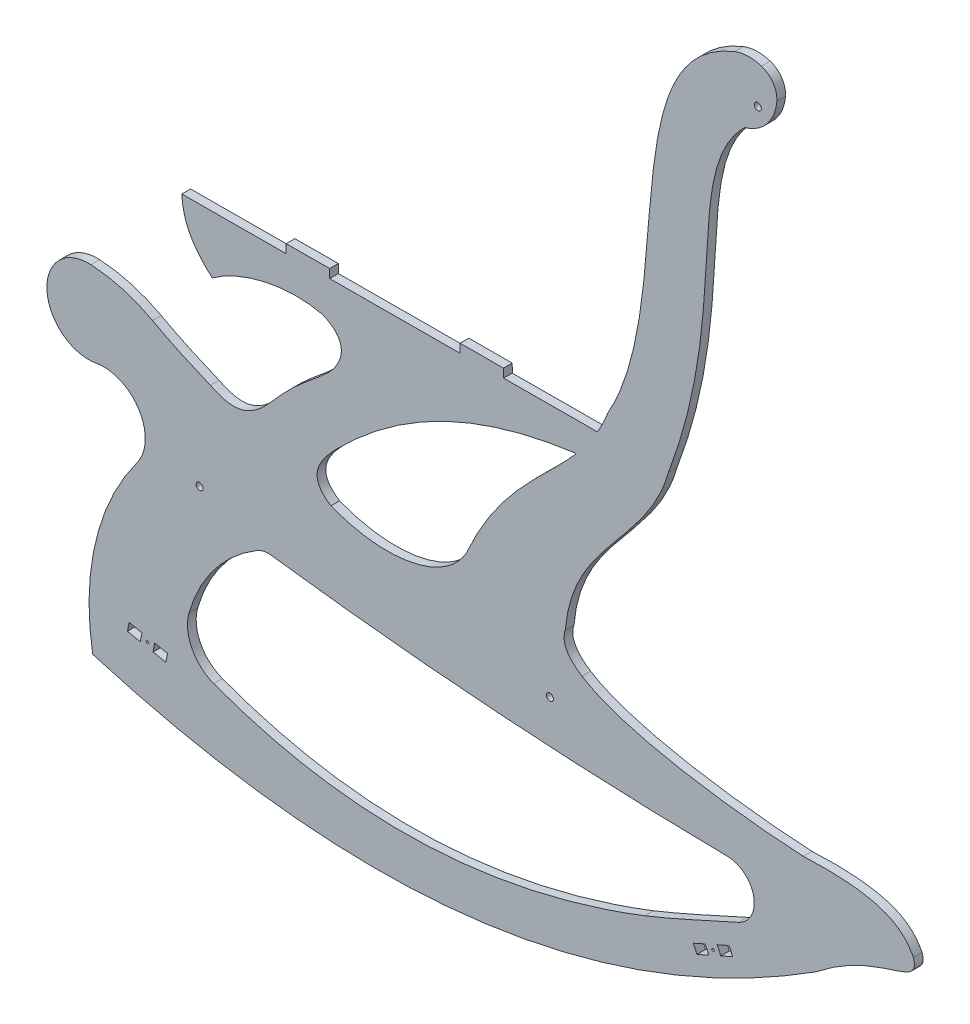
SolidWorks part; units mm, degrees
material "Teak"
ref_plane "Front Plane" through (0, 0, 0) normal (0, 0, 1) x (1, 0, 0)
ref_plane "Top Plane" through (0, 0, 0) normal (0, 1, 0) x (1, 0, 0)
ref_plane "Right Plane" through (0, 0, 0) normal (1, 0, 0) x (0, 0, -1)
sketch "Несущая боковая" plane through (0, 0, 0) normal (0, 0, 1) x (1, 0, 0)
  line L6 (398.785, -200.6515) -> (-79.2948, -202.7)
  arc A0 (568.0858, 187.1743) -> (604.9253, 231.748) centre (555.0835, 235.431) ccw
  arc A1 (604.9253, 231.748) -> (587.3016, 257.9076) centre (579.4885, 233.6276) ccw
  arc A2 (587.3016, 257.9076) -> (556.344, 256.9224) centre (573.2016, 214.0906) ccw
  arc A4 (-130.7033, -495.9282) -> (-177.7889, -420.4808) centre (-169.1009, -467.4752) ccw
  arc A7 (-130.7033, -495.9282) -> (-181.6944, -712.4375) centre (95.3308, -663.4217) ccw
  arc A8 (-183.8786, -325.353) -> (-177.7889, -420.4808) centre (-186.515, -373.2806) ccw
  arc A9 (-112.9747, -345.6094) -> (-183.8786, -325.353) centre (-193.0224, -491.581) ccw
  arc A10 (560.3467, -608.2215) -> (548.1989, -548.57) centre (547.8281, -579.7082) ccw
  arc A11 (23.5507, -511.1423) -> (548.1989, -548.57) centre (601.0308, 3887.8918) ccw
  arc A12 (7.2112, -514.4863) -> (-70.9864, -615.6156) centre (95.3308, -663.4217) ccw
  arc A13 (-70.9864, -615.6156) -> (-42.6063, -671.9817) centre (-26.3207, -628.4543) ccw
  arc A14 (23.5507, -511.1423) -> (7.2112, -514.4863) centre (20.2245, -536.4807) ccw
  spline S0 degree 3 poles (556.344, 256.9224) (413.4931, 200.7) (492.8039, -30.4464) (410.7267, -175.5993) knots 0.000401 0.000401 0.000401 0.000401 0.043478 0.043478 0.043478 0.043478
  spline S1 degree 3 poles (410.7267, -175.5993) (407.231, -184.6492) (403.2193, -192.9282) (398.785, -200.6515) knots 0.043478 0.043478 0.043478 0.043478 0.086957 0.086957 0.086957 0.086957
  spline S2 degree 3 poles (-79.2948, -202.7) (-78.5172, -227.7) (-66.7741, -249.7094) (-44.1772, -268.7587) knots 0.130435 0.130435 0.130435 0.130435 0.173913 0.173913 0.173913 0.173913
  spline S3 degree 3 poles (-44.1772, -268.7587) (-12.7058, -245.829) (38.9597, -231.7344) (82.6666, -241.804) knots 0.173913 0.173913 0.173913 0.173913 0.217391 0.217391 0.217391 0.217391
  spline S4 degree 3 poles (82.6666, -241.804) (105.6787, -251.6525) (111.2464, -268.6919) (94.2115, -290.7234) knots 0.217391 0.217391 0.217391 0.217391 0.26087 0.26087 0.26087 0.26087
  spline S5 degree 3 poles (94.2115, -290.7234) (87.1581, -299.8457) (74.9831, -308.4217) (61.0599, -320.5021) knots 0.26087 0.26087 0.26087 0.26087 0.304348 0.304348 0.304348 0.304348
  spline S6 degree 3 poles (61.0599, -320.5021) (47.3806, -331.8412) (34.8832, -345.2678) (22.8705, -359.1067) knots 0.304348 0.304348 0.304348 0.304348 0.347826 0.347826 0.347826 0.347826
  spline S7 degree 3 poles (22.8705, -359.1067) (-5.5844, -391.8897) (-25.5922, -386.6363) (-46.4172, -376.7876) knots 0.347826 0.347826 0.347826 0.347826 0.391304 0.391304 0.391304 0.391304
  spline S8 degree 3 poles (-46.4172, -376.7876) (-71.9902, -366.2219) (-92.784, -356.6815) (-112.9747, -345.6094) knots 0.391304 0.391304 0.391304 0.391304 0.434783 0.434783 0.434783 0.434783
  spline S14 degree 3 poles (-181.6944, -712.4375) (138.4622, -807.7317) (410.6911, -765.399) (650.1904, -612.5982) knots 0.652174 0.652174 0.652174 0.652174 0.695652 0.695652 0.695652 0.695652
  spline S15 degree 3 poles (650.1904, -612.5982) (721.7263, -555.1366) (771.3742, -572.8028) (761.971, -542.4383) knots 0.695652 0.695652 0.695652 0.695652 0.73913 0.73913 0.73913 0.73913
  spline S16 degree 3 poles (761.971, -542.4383) (749.9881, -518.2511) (723.1034, -500.8362) (635.2399, -505.0064) knots 0.73913 0.73913 0.73913 0.73913 0.782609 0.782609 0.782609 0.782609
  spline S17 degree 3 poles (635.2399, -505.0064) (572.992, -501.9328) (433.5503, -486.7788) (380.9104, -452.9037) knots 0.782609 0.782609 0.782609 0.782609 0.826087 0.826087 0.826087 0.826087
  spline S18 degree 3 poles (380.9104, -452.9037) (364.7659, -442.5143) (356.7862, -430.3638) (361.7026, -416.2609) knots 0.826087 0.826087 0.826087 0.826087 0.869565 0.869565 0.869565 0.869565
  spline S19 degree 3 poles (361.7026, -416.2609) (369.7577, -319.5618) (455.7474, -287.137) (480.2427, -200.3025) knots 0.869565 0.869565 0.869565 0.869565 0.913043 0.913043 0.913043 0.913043
  spline S20 degree 3 poles (480.2427, -200.3025) (553.5443, -5.6015) (495.01, 115.2768) (568.0858, 187.1743) knots 0.913043 0.913043 0.913043 0.913043 0.956522 0.956522 0.956522 0.956522
  spline S25 degree 3 poles (452.9574, -655.3702) (274.7112, -724.495) (109.7393, -728.981) (-42.6063, -671.9817) knots 0.555556 0.555556 0.555556 0.555556 0.666667 0.666667 0.666667 0.666667
  spline S26 degree 3 poles (560.3467, -608.2215) (524.5503, -623.9377) (490.7002, -640.4881) (452.9574, -655.3702) knots 0.444444 0.444444 0.444444 0.444444 0.555556 0.555556 0.555556 0.555556
  spline S31 degree 3 poles (97.4618, -368.9486) (168.6207, -296.3511) (255.442, -250.0892) (374.5085, -234.3308) knots 0.75 0.75 0.75 0.75 1 1 1 1
  spline S32 degree 3 poles (92.0908, -427.5464) (69.7947, -412.5311) (70.4905, -396.4567) (97.4618, -368.9486) knots 0.5 0.5 0.5 0.5 0.75 0.75 0.75 0.75
  spline S33 degree 3 poles (247.8827, -396.6458) (222.4754, -441.0979) (152.6914, -451.7196) (92.0908, -427.5464) knots 0.25 0.25 0.25 0.25 0.5 0.5 0.5 0.5
  spline S34 degree 3 poles (374.5085, -234.3308) (336.7044, -278.0035) (285.6362, -310.9643) (247.8827, -396.6458) knots 0 0 0 0 0.25 0.25 0.25 0.25
  dimension "D2" = 48
sketch "Боковая под поперечины" [suppressed] plane through (0, 0, 0) normal (0, 0, 1) x (1, 0, 0)
  line L15 (-159.6049, -346.9107) -> (-207.6507, -344.8161) construction
  line L16 (-207.6507, -344.8161) -> (-218.5759, -409.003)
  line L56 (-207.6507, -344.8161) -> (-159.6963, -346.9068)
  line L57 (-159.6963, -346.9068) -> (-148.2015, -350.3521)
  line L58 (-148.2015, -350.3521) -> (-104.2437, -369.6319)
  line L59 (-104.2437, -369.6319) -> (-95.353, -374.2095)
  line L60 (-95.353, -374.2095) -> (-51.5894, -393.9261)
  line L61 (-51.5894, -393.9261) -> (-42.3459, -397.7417)
  line L62 (-42.3459, -397.7417) -> (2.1537, -415.7357)
  line L63 (2.1537, -415.7357) -> (11.4455, -419.432)
  line L64 (11.4455, -419.432) -> (56.3986, -436.2612)
  line L65 (56.3986, -436.2612) -> (65.8381, -439.5619)
  line L66 (65.8381, -439.5619) -> (111.7403, -453.5971)
  line L67 (111.7403, -453.5971) -> (121.3499, -456.3643)
  line L68 (121.3499, -456.3643) -> (169.2689, -459.1514)
  line L69 (169.2689, -459.1514) -> (179.2066, -458.0374)
  line L70 (179.2066, -458.0374) -> (224.5179, -442.198)
  line L71 (224.5179, -442.198) -> (232.8956, -436.7378)
  line L72 (232.8956, -436.7378) -> (261.7321, -398.3651)
  line L73 (261.7321, -398.3651) -> (267.2053, -389.9959)
  line L74 (267.2053, -389.9959) -> (294.9373, -350.8177)
  line L75 (294.9373, -350.8177) -> (300.8954, -342.7864)
  line L76 (300.8954, -342.7864) -> (330.585, -305.0699)
  line L77 (330.585, -305.0699) -> (336.9867, -297.3877)
  line L78 (336.9867, -297.3877) -> (368.9263, -261.5566)
  line L79 (368.9263, -261.5566) -> (376.1332, -254.6241)
  line L80 (376.1332, -254.6241) -> (406.9239, -217.801)
  line L81 (406.9239, -217.801) -> (412.4436, -209.4624)
  line L82 (412.4436, -209.4624) -> (434.4129, -166.7851)
  line L83 (438.0837, -157.4832) -> (452.6073, -111.7332)
  line L84 (452.6073, -111.7332) -> (454.9033, -102.0003)
  line L85 (454.9033, -102.0003) -> (464.25, -54.9191)
  line L86 (464.25, -54.9191) -> (465.6878, -45.023)
  line L87 (465.6878, -45.023) -> (472.014, 2.5582)
  line L88 (472.014, 2.5582) -> (473.0512, 12.5043)
  line L89 (473.0512, 12.5043) -> (478.3742, 60.2082)
  line L90 (478.3742, 60.2082) -> (479.4656, 70.1485)
  line L91 (479.4656, 70.1485) -> (486.2184, 117.6711)
  line L92 (486.2184, 117.6711) -> (487.9962, 127.5118)
  line L93 (487.9962, 127.5118) -> (500.2801, 173.9134)
  line L94 (500.2801, 173.9134) -> (504.8877, 188.1882)
  line L95 (504.8877, 188.1882) -> (532.6089, 227.3741)
  line L96 (532.6089, 227.3741) -> (546.1164, 235.9502)
  line L97 (546.1164, 235.9502) -> (589.1375, 257.2382)
  line L99 (434.4129, -166.7851) -> (438.0837, -157.4832)
  arc A4 (568.0858, 187.1743) -> (604.9253, 231.748) centre (554.9668, 235.5274) ccw
  arc A7 (604.9253, 231.748) -> (589.1375, 257.2382) centre (579.4223, 233.5866) ccw
  arc A10 (604.9253, 231.748) -> (587.3016, 257.9076) centre (579.4885, 233.6276) ccw construction
  arc A11 (-121.8206, -474.4411) -> (-17.3364, -532.0713) centre (-58.8058, -483.7252) ccw
  arc A12 (7.2112, -514.4863) -> (-17.3364, -532.0713) centre (95.3308, -663.4217) ccw
  arc A13 (23.5507, -511.1423) -> (7.2112, -514.4863) centre (20.2245, -536.4807) ccw
  arc A15 (-121.8206, -474.4411) -> (-177.7889, -420.4808) centre (-169.1009, -467.4752) ccw
  arc A16 (23.5507, -511.1423) -> (341.0431, -541.2606) centre (601.0308, 3887.8918) ccw
  arc A17 (-130.7033, -495.9282) -> (-177.7889, -420.4808) centre (-169.1009, -467.4752) ccw construction
  arc A18 (-183.8786, -325.353) -> (-177.7889, -420.4808) centre (-186.515, -373.2806) ccw construction
  arc A19 (-218.5759, -409.003) -> (-177.7889, -420.4808) centre (-186.515, -373.2806) ccw
  arc A20 (23.5507, -511.1423) -> (548.1989, -548.57) centre (601.0308, 3887.8918) ccw construction
  arc A21 (23.5507, -511.1423) -> (7.2112, -514.4863) centre (20.2245, -536.4807) ccw construction
  arc A22 (7.2112, -514.4863) -> (-70.9864, -615.6156) centre (95.3308, -663.4217) ccw construction
  arc A23 (341.0431, -541.2606) -> (375.7523, -454.4299) centre (343.931, -492.0624) ccw
  spline S13 degree 3 poles (375.7523, -454.4299) (361.34, -442.2431) (355.1113, -429.3811) (361.7026, -416.2609) knots 0.5 0.5 0.5 0.5 0.533333 0.533333 0.533333 0.533333
  spline S14 degree 3 poles (361.7026, -416.2609) (369.7577, -319.5618) (455.7474, -287.137) (480.2427, -200.3025) knots 0.533333 0.533333 0.533333 0.533333 0.566667 0.566667 0.566667 0.566667
  spline S15 degree 3 poles (480.2427, -200.3025) (553.5444, -5.6014) (495.0101, 115.2768) (568.0858, 187.1743) knots 0.566667 0.566667 0.566667 0.566667 0.6 0.6 0.6 0.6
  point P66 (608.2751, 264.1653)
  point P67 (553.7309, 240.2756)
  point P74 (-221.3236, -344.22)
  dimension "D1" = 48
  dimension "D2" = 12
  dimension "D3" = 10
  dimension "D10" = 16
  dimension "D11" = 15
extrude "Несущая" add sketch "Несущая боковая" along normal blind 10
extrude "Боковая" [suppressed] add sketch "Боковая под поперечины" along normal blind 10
sketch "Sketch3" [suppressed] plane through (0, 0, 0) normal (0, 0, 1) x (1, 0, 0)
  line L0 (546.1164, 235.9502) -> (589.1375, 257.2382) construction
  line L2 (-206.3501, -396.7709) -> (-202.6586, -375.0829)
  line L3 (-216.2083, -395.093) -> (-212.5168, -373.4049)
  line L6 (-216.2083, -395.093) -> (-206.3501, -396.7709)
  line L10 (-207.6507, -344.8161) -> (-194.6631, -345.3823) construction
  line L11 (-207.6507, -344.8161) -> (-208.0863, -354.8066) construction
  line L12 (-159.6963, -346.9068) -> (-160.1319, -356.8973) construction
  line L13 (-208.0863, -354.8066) -> (-195.0986, -355.3728) construction
  line L14 (-194.6631, -345.3823) -> (-195.0986, -355.3728)
  line L15 (-172.684, -346.3405) -> (-173.1195, -356.331)
  line L16 (-173.1195, -356.331) -> (-160.1319, -356.8973) construction
  line L17 (-195.0986, -355.3728) -> (-173.1195, -356.331)
  line L18 (-172.684, -346.3405) -> (-159.6963, -346.9068) construction
  line L19 (-194.6631, -345.3823) -> (-172.684, -346.3405)
  line L37 (-136.2963, -355.5737) -> (-140.3129, -364.7316)
  line L38 (-116.149, -364.4103) -> (-120.1656, -373.5681)
  line L40 (-152.2182, -359.51) -> (-140.3129, -364.7316) construction
  line L41 (-116.149, -364.4103) -> (-104.2437, -369.6319) construction
  line L42 (-140.3129, -364.7316) -> (-120.1656, -373.5681)
  line L43 (-104.2437, -369.6319) -> (-108.2603, -378.7897) construction
  line L44 (-120.1656, -373.5681) -> (-108.2603, -378.7897) construction
  line L45 (-148.2015, -350.3521) -> (-136.2963, -355.5737) construction
  line L46 (-136.2963, -355.5737) -> (-116.149, -364.4103)
  line L47 (-148.2015, -350.3521) -> (-152.2182, -359.51) construction
  line L48 (-104.2437, -369.6319) -> (-148.2015, -350.3521) construction
  line L49 (-63.442, -388.5862) -> (-67.5496, -397.7036)
  line L50 (-83.5003, -379.5494) -> (-63.442, -388.5862)
  line L51 (-83.5003, -379.5494) -> (-87.608, -388.6668)
  line L52 (-63.442, -388.5862) -> (-51.5894, -393.9261) construction
  line L53 (-99.4606, -383.3269) -> (-87.608, -388.6668) construction
  line L54 (-51.5894, -393.9261) -> (-55.697, -403.0436) construction
  line L55 (-95.353, -374.2095) -> (-83.5003, -379.5494) construction
  line L56 (-87.608, -388.6668) -> (-67.5496, -397.7036)
  line L57 (-67.5496, -397.7036) -> (-55.697, -403.0436) construction
  line L58 (-95.353, -374.2095) -> (-99.4606, -383.3269) construction
  line L59 (-34.0427, -411.8858) -> (-13.647, -420.1331)
  line L60 (-30.2939, -402.615) -> (-9.8983, -410.8623)
  line L61 (-42.3459, -397.7417) -> (-30.2939, -402.615) construction
  line L62 (-9.8983, -410.8623) -> (2.1537, -415.7357) construction
  line L63 (-46.0946, -407.0124) -> (-34.0427, -411.8858) construction
  line L64 (-9.8983, -410.8623) -> (-13.647, -420.1331)
  line L65 (-42.3459, -397.7417) -> (-46.0946, -407.0124) construction
  line L66 (-13.647, -420.1331) -> (-1.595, -425.0064) construction
  line L67 (-30.2939, -402.615) -> (-34.0427, -411.8858)
  line L68 (2.1537, -415.7357) -> (-1.595, -425.0064) construction
  line L69 (44.2238, -431.7033) -> (40.7177, -441.0685)
  line L70 (56.3986, -436.2612) -> (52.8925, -445.6264) construction
  line L71 (23.6203, -423.9899) -> (44.2238, -431.7033)
  line L72 (23.6203, -423.9899) -> (20.1142, -433.3551)
  line L73 (7.9394, -428.7972) -> (20.1142, -433.3551) construction
  line L74 (11.4455, -419.432) -> (23.6203, -423.9899) construction
  line L75 (44.2238, -431.7033) -> (56.3986, -436.2612) construction
  line L76 (11.4455, -419.432) -> (7.9394, -428.7972) construction
  line L77 (40.7177, -441.0685) -> (52.8925, -445.6264) construction
  line L78 (20.1142, -433.3551) -> (40.7177, -441.0685)
  line L79 (96.3845, -459.3589) -> (108.8163, -463.1601) construction
  line L80 (65.8381, -439.5619) -> (62.9141, -449.1249) construction
  line L81 (99.3085, -449.7959) -> (96.3845, -459.3589)
  line L82 (78.27, -443.3631) -> (75.346, -452.9261)
  line L83 (65.8381, -439.5619) -> (78.27, -443.3631) construction
  line L84 (62.9141, -449.1249) -> (75.346, -452.9261) construction
  line L85 (99.3085, -449.7959) -> (111.7403, -453.5971) construction
  line L86 (111.7403, -453.5971) -> (108.8163, -463.1601) construction
  line L87 (75.346, -452.9261) -> (96.3845, -459.3589)
  line L88 (78.27, -443.3631) -> (99.3085, -449.7959)
  line L89 (120.7692, -466.3474) -> (133.7473, -467.1023) construction
  line L90 (156.2908, -458.3965) -> (169.2689, -459.1514) construction
  line L91 (133.7473, -467.1023) -> (155.7102, -468.3797)
  line L92 (156.2908, -458.3965) -> (155.7102, -468.3797)
  line L93 (155.7102, -468.3797) -> (168.6882, -469.1345) construction
  line L94 (121.3499, -456.3643) -> (134.3279, -457.1191) construction
  line L95 (134.3279, -457.1191) -> (156.2908, -458.3965)
  line L96 (121.3499, -456.3643) -> (120.7692, -466.3474) construction
  line L97 (134.3279, -457.1191) -> (133.7473, -467.1023)
  line L98 (169.2689, -459.1514) -> (168.6882, -469.1345) construction
  line L99 (215.546, -455.9277) -> (227.8178, -451.6378) construction
  line L100 (191.4784, -453.7475) -> (212.2461, -446.4878)
  line L101 (191.4784, -453.7475) -> (194.7783, -463.1874)
  line L102 (182.5065, -467.4772) -> (194.7783, -463.1874) construction
  line L103 (224.5179, -442.198) -> (227.8178, -451.6378) construction
  line L104 (194.7783, -463.1874) -> (215.546, -455.9277)
  line L105 (179.2066, -458.0374) -> (182.5065, -467.4772) construction
  line L106 (212.2461, -446.4878) -> (224.5179, -442.198) construction
  line L107 (179.2066, -458.0374) -> (191.4784, -453.7475) construction
  line L108 (212.2461, -446.4878) -> (215.546, -455.9277)
  line L109 (248.6998, -432.3528) -> (261.9165, -414.7653)
  line L110 (261.9165, -414.7653) -> (269.7264, -404.3728) construction
  line L111 (240.8899, -442.7454) -> (248.6998, -432.3528) construction
  line L112 (240.7055, -426.3452) -> (248.6998, -432.3528)
  line L113 (253.9222, -408.7577) -> (261.7321, -398.3651) construction
  line L114 (261.7321, -398.3651) -> (269.7264, -404.3728) construction
  line L115 (232.8956, -436.7378) -> (240.7055, -426.3452) construction
  line L116 (240.7055, -426.3452) -> (253.9222, -408.7577)
  line L117 (232.8956, -436.7378) -> (240.8899, -442.7454) construction
  line L118 (253.9222, -408.7577) -> (261.9165, -414.7653)
  line L119 (267.2053, -389.9959) -> (274.7161, -379.3851) construction
  line L120 (267.2053, -389.9959) -> (275.3674, -395.7734) construction
  line L121 (275.3674, -395.7734) -> (282.8782, -385.1626) construction
  line L122 (274.7161, -379.3851) -> (282.8782, -385.1626)
  line L123 (282.8782, -385.1626) -> (295.5887, -367.2059)
  line L124 (287.4266, -361.4284) -> (295.5887, -367.2059)
  line L125 (294.9373, -350.8177) -> (303.0995, -356.5952) construction
  line L126 (295.5887, -367.2059) -> (303.0995, -356.5952) construction
  line L127 (287.4266, -361.4284) -> (294.9373, -350.8177) construction
  line L128 (274.7161, -379.3851) -> (287.4266, -361.4284)
  line L129 (330.4016, -321.4701) -> (338.4426, -311.2553) construction
  line L130 (316.7939, -338.7569) -> (330.4016, -321.4701)
  line L131 (308.9363, -332.5715) -> (322.5441, -315.2848)
  line L132 (300.8954, -342.7864) -> (308.9363, -332.5715) construction
  line L133 (300.8954, -342.7864) -> (308.753, -348.9717) construction
  line L134 (308.9363, -332.5715) -> (316.7939, -338.7569)
  line L135 (322.5441, -315.2848) -> (330.4016, -321.4701)
  line L136 (308.753, -348.9717) -> (316.7939, -338.7569) construction
  line L137 (330.585, -305.0699) -> (338.4426, -311.2553) construction
  line L138 (322.5441, -315.2848) -> (330.585, -305.0699) construction
  line L139 (336.9867, -297.3877) -> (344.4515, -304.0418) construction
  line L140 (360.276, -271.2609) -> (367.7408, -277.915)
  line L141 (367.7408, -277.915) -> (376.3911, -268.2107) construction
  line L142 (344.4515, -304.0418) -> (353.1018, -294.3375) construction
  line L143 (353.1018, -294.3375) -> (367.7408, -277.915)
  line L144 (336.9867, -297.3877) -> (345.637, -287.6834) construction
  line L145 (368.9263, -261.5566) -> (376.3911, -268.2107) construction
  line L146 (360.276, -271.2609) -> (368.9263, -261.5566) construction
  line L147 (345.637, -287.6834) -> (360.276, -271.2609)
  line L148 (345.637, -287.6834) -> (353.1018, -294.3375)
  line L149 (406.2562, -234.1886) -> (414.5953, -224.2157) construction
  line L150 (398.5847, -227.7739) -> (406.2562, -234.1886)
  line L151 (392.1438, -251.0659) -> (406.2562, -234.1886)
  line L152 (383.8047, -261.0388) -> (392.1438, -251.0659) construction
  line L153 (406.9239, -217.801) -> (414.5953, -224.2157) construction
  line L154 (376.1332, -254.6241) -> (384.4724, -244.6512) construction
  line L155 (376.1332, -254.6241) -> (383.8047, -261.0388) construction
  line L156 (398.5847, -227.7739) -> (406.9239, -217.801) construction
  line L157 (384.4724, -244.6512) -> (392.1438, -251.0659)
  line L158 (384.4724, -244.6512) -> (398.5847, -227.7739)
  line L159 (437.354, -182.9205) -> (443.304, -171.3621) construction
  line L160 (428.4629, -178.3436) -> (434.4129, -166.7851) construction
  line L161 (428.4629, -178.3436) -> (437.354, -182.9205)
  line L162 (418.3936, -197.904) -> (427.2847, -202.4809)
  line L163 (427.2847, -202.4809) -> (437.354, -182.9205)
  line L164 (412.4436, -209.4624) -> (421.3346, -214.0393) construction
  line L165 (421.3346, -214.0393) -> (427.2847, -202.4809) construction
  line L166 (434.4129, -166.7851) -> (443.304, -171.3621) construction
  line L167 (418.3936, -197.904) -> (428.4629, -178.3436)
  line L168 (412.4436, -209.4624) -> (418.3936, -197.904) construction
  line L169 (447.6149, -160.509) -> (451.5484, -148.1183) construction
  line L170 (448.6738, -124.1238) -> (452.6073, -111.7332) construction
  line L171 (442.0172, -145.0926) -> (451.5484, -148.1183)
  line L172 (448.6738, -124.1238) -> (458.205, -127.1496)
  line L173 (438.0837, -157.4832) -> (442.0172, -145.0926) construction
  line L174 (458.205, -127.1496) -> (462.1385, -114.7589) construction
  line L175 (442.0172, -145.0926) -> (448.6738, -124.1238)
  line L176 (452.6073, -111.7332) -> (462.1385, -114.7589) construction
  line L177 (438.0837, -157.4832) -> (447.6149, -160.509) construction
  line L178 (451.5484, -148.1183) -> (458.205, -127.1496)
  line L179 (-51.5894, -393.9261) -> (-95.353, -374.2095) construction
  line L180 (2.1537, -415.7357) -> (-42.3459, -397.7417) construction
  line L181 (56.3986, -436.2612) -> (11.4455, -419.432) construction
  line L182 (368.9263, -261.5566) -> (336.9867, -297.3877) construction
  line L183 (406.9239, -217.801) -> (376.1332, -254.6241) construction
  line L184 (434.4129, -166.7851) -> (412.4436, -209.4624) construction
  line L185 (452.6073, -111.7332) -> (438.0837, -157.4832) construction
  line L186 (464.7118, -103.9476) -> (467.2432, -91.1964) construction
  line L187 (457.4347, -89.2492) -> (461.7186, -67.6703)
  line L188 (454.9033, -102.0003) -> (457.4347, -89.2492) construction
  line L189 (457.4347, -89.2492) -> (467.2432, -91.1964)
  line L190 (461.7186, -67.6703) -> (464.25, -54.9191) construction
  line L191 (454.9033, -102.0003) -> (464.7118, -103.9476) construction
  line L192 (464.25, -54.9191) -> (474.0586, -56.8664) construction
  line L193 (467.2432, -91.1964) -> (471.5272, -69.6175)
  line L194 (461.7186, -67.6703) -> (471.5272, -69.6175)
  line L195 (471.5272, -69.6175) -> (474.0586, -56.8664) construction
  line L196 (467.4011, -32.1364) -> (470.3006, -10.3284)
  line L197 (465.6878, -45.023) -> (467.4011, -32.1364) construction
  line L198 (472.014, 2.5582) -> (481.9268, 1.2403) construction
  line L199 (477.3139, -33.4544) -> (480.2134, -11.6463)
  line L200 (470.3006, -10.3284) -> (472.014, 2.5582) construction
  line L201 (480.2134, -11.6463) -> (481.9268, 1.2403) construction
  line L202 (465.6878, -45.023) -> (475.6006, -46.341) construction
  line L203 (467.4011, -32.1364) -> (477.3139, -33.4544)
  line L204 (470.3006, -10.3284) -> (480.2134, -11.6463)
  line L205 (475.6006, -46.341) -> (477.3139, -33.4544) construction
  line L206 (473.0512, 12.5043) -> (474.4928, 25.4241) construction
  line L207 (474.4928, 25.4241) -> (476.9325, 47.2884)
  line L208 (473.0512, 12.5043) -> (482.9895, 11.3953) construction
  line L209 (486.8708, 46.1795) -> (488.3125, 59.0993) construction
  line L210 (476.9325, 47.2884) -> (486.8708, 46.1795)
  line L211 (474.4928, 25.4241) -> (484.4311, 24.3152)
  line L212 (482.9895, 11.3953) -> (484.4311, 24.3152) construction
  line L213 (484.4311, 24.3152) -> (486.8708, 46.1795)
  line L214 (478.3742, 60.2082) -> (488.3125, 59.0993) construction
  line L215 (476.9325, 47.2884) -> (478.3742, 60.2082) construction
  line L216 (486.2184, 117.6711) -> (496.119, 116.2643) construction
  line L217 (481.2945, 83.0192) -> (484.3895, 104.8004)
  line L218 (491.195, 81.6124) -> (494.2901, 103.3936)
  line L219 (494.2901, 103.3936) -> (496.119, 116.2643) construction
  line L220 (484.3895, 104.8004) -> (486.2184, 117.6711) construction
  line L221 (484.3895, 104.8004) -> (494.2901, 103.3936)
  line L222 (479.4656, 70.1485) -> (481.2945, 83.0192) construction
  line L223 (479.4656, 70.1485) -> (489.3661, 68.7417) construction
  line L224 (481.2945, 83.0192) -> (491.195, 81.6124)
  line L225 (489.3661, 68.7417) -> (491.195, 81.6124) construction
  line L226 (500.2801, 173.9134) -> (509.9471, 171.3543) construction
  line L227 (497.6632, 124.9527) -> (500.9901, 137.5198) construction
  line L228 (491.3231, 140.0789) -> (496.9532, 161.3463)
  line L229 (506.6202, 158.7872) -> (509.9471, 171.3543) construction
  line L230 (487.9962, 127.5118) -> (491.3231, 140.0789) construction
  line L231 (487.9962, 127.5118) -> (497.6632, 124.9527) construction
  line L232 (491.3231, 140.0789) -> (500.9901, 137.5198)
  line L233 (496.9532, 161.3463) -> (506.6202, 158.7872)
  line L234 (500.9901, 137.5198) -> (506.6202, 158.7872)
  line L235 (496.9532, 161.3463) -> (500.2801, 173.9134) construction
  line L236 (512.3955, 198.8011) -> (525.1011, 216.7613)
  line L237 (504.8877, 188.1882) -> (513.0514, 182.413) construction
  line L238 (525.1011, 216.7613) -> (532.6089, 227.3741) construction
  line L239 (512.3955, 198.8011) -> (520.5593, 193.0258)
  line L240 (525.1011, 216.7613) -> (533.2648, 210.986)
  line L241 (532.6089, 227.3741) -> (540.7726, 221.5989) construction
  line L242 (504.8877, 188.1882) -> (512.3955, 198.8011) construction
  line L243 (533.2648, 210.986) -> (540.7726, 221.5989) construction
  line L244 (513.0514, 182.413) -> (520.5593, 193.0258) construction
  line L245 (520.5593, 193.0258) -> (533.2648, 210.986)
  line L246 (589.1375, 257.2382) -> (593.5725, 248.2755) construction
  line L247 (557.7679, 241.7157) -> (562.2029, 232.7529)
  line L248 (546.1164, 235.9502) -> (557.7679, 241.7157) construction
  line L249 (577.4859, 251.4727) -> (581.9209, 242.51)
  line L250 (581.9209, 242.51) -> (593.5725, 248.2755) construction
  line L251 (557.7679, 241.7157) -> (577.4859, 251.4727)
  line L252 (546.1164, 235.9502) -> (550.5514, 226.9874) construction
  line L253 (562.2029, 232.7529) -> (581.9209, 242.51)
  line L254 (577.4859, 251.4727) -> (589.1375, 257.2382) construction
  line L255 (550.5514, 226.9874) -> (562.2029, 232.7529) construction
  line L256 (464.25, -54.9191) -> (454.9033, -102.0003) construction
  line L257 (472.014, 2.5582) -> (465.6878, -45.023) construction
  line L258 (486.2184, 117.6711) -> (479.4656, 70.1485) construction
  line L259 (500.2801, 173.9134) -> (487.9962, 127.5118) construction
  line L260 (487.9962, 127.5118) -> (486.2184, 117.6711) construction
  line L261 (532.6089, 227.3741) -> (504.8877, 188.1882) construction
  line L262 (504.8877, 188.1882) -> (500.2801, 173.9134) construction
  line L264 (-212.5168, -373.4049) -> (-202.6586, -375.0829)
  line L269 (-207.6507, -344.8161) -> (-218.5759, -409.003) construction
  point P1 (-214.3626, -384.2489)
  dimension "D1" = 40
  dimension "D2" = 10
  dimension "D3" = 22
extrude "Шипы" [suppressed] cut sketch "Sketch3" along normal through all
sketch "Sketch4" [suppressed] plane through (0, 0, 10) normal (0, 0, 1) x (1, 0, 0)
  line L0 (-208.4348, -362.799) -> (-221.0097, -388.653) construction
  line L1 (-221.0097, -388.653) -> (-207.6507, -344.8161) construction
  line L2 (-207.6507, -344.8161) -> (-208.4348, -362.799) construction
  line L4 (-217.7838, -439.8154) -> (-237.4507, -429.7729) construction
  line L5 (-237.4507, -429.7729) -> (-240.164, -452.0896) construction
  line L6 (-240.164, -452.0896) -> (-201.8347, -418.7702) construction
  arc A1 (-218.5759, -409.003) -> (-177.7889, -420.4808) centre (-186.515, -373.2806) ccw construction
extrude "Излишки" [suppressed] cut sketch "Sketch4" against normal up to next
sketch "Sketch5" plane through (0, 0, 10) normal (0, 0, 1) x (1, 0, 0)
  line L1 (40.6613, -192.1859) -> (90.6608, -191.9717)
  line L2 (40.6613, -192.1859) -> (40.7041, -202.1858)
  line L3 (40.7041, -202.1858) -> (90.7037, -201.9716)
  line L4 (90.6608, -191.9717) -> (90.7037, -201.9716)
  line L5 (398.785, -200.6515) -> (-79.2948, -202.7) construction
  line L6 (240.6594, -191.329) -> (290.659, -191.1147)
  line L7 (240.6594, -191.329) -> (240.7023, -201.3289)
  line L8 (240.7023, -201.3289) -> (290.7018, -201.1146)
  line L9 (290.659, -191.1147) -> (290.7018, -201.1146)
  dimension "D1" = 10
  dimension "D2" = 150
  dimension "D3" = 120
  dimension "D4" = 50
extrude "Шипы на подлокотниках" add sketch "Sketch5" against normal up to surface (10 mm away) up to face at (168.5307, -593.8353, 0)
sketch "Sketch6" plane through (0, 0, 10) normal (0, 0, 1) x (1, 0, 0)
  line L0 (-139.8462, -659.6686) -> (-141.8053, -669.4748)
  line L1 (-141.8053, -669.4748) -> (-127.0959, -672.4134)
  line L2 (-127.0959, -672.4134) -> (-125.1369, -662.6072)
  line L3 (-125.1369, -662.6072) -> (-139.8462, -659.6686)
  line L4 (-127.0959, -672.4134) -> (-112.3866, -675.352) construction
  line L5 (-112.3866, -675.352) -> (-110.4276, -665.5457)
  line L6 (-110.4276, -665.5457) -> (-95.7182, -668.4843)
  line L7 (-95.7182, -668.4843) -> (-97.6773, -678.2905)
  line L8 (-97.6773, -678.2905) -> (-112.3866, -675.352)
  line L9 (-119.7413, -673.8827) -> (-117.7822, -664.0765) construction
  line L10 (-125.1369, -662.6072) -> (-110.4276, -665.5457) construction
  line L11 (-126.1164, -667.5103) -> (-111.4071, -670.4489) construction
  line L12 (522.6672, -648.5899) -> (536.3744, -642.4979) construction
  line L13 (554.1429, -645.5439) -> (540.4358, -651.636)
  line L14 (533.5822, -654.682) -> (529.5208, -645.5439) construction
  line L15 (522.6672, -648.5899) -> (508.96, -654.682)
  line L16 (513.0214, -663.8201) -> (526.7286, -657.728)
  line L17 (526.7286, -657.728) -> (540.4358, -651.636) construction
  line L18 (526.7286, -657.728) -> (522.6672, -648.5899)
  line L19 (540.4358, -651.636) -> (536.3744, -642.4979)
  line L20 (524.6979, -653.159) -> (538.4051, -647.0669) construction
  line L21 (550.0815, -636.4058) -> (554.1429, -645.5439)
  line L22 (508.96, -654.682) -> (513.0214, -663.8201)
  line L23 (536.3744, -642.4979) -> (550.0815, -636.4058)
  circle A2 centre (531.5515, -650.113) radius 1.5
  circle A4 centre (-118.7618, -668.9796) radius 1.5
  dimension "D1" = 10
  dimension "D4" = 3
  dimension "D6" = 3
  dimension "D2" = 15
  dimension "D5" = 15
extrude "Под ребра жесткости" cut sketch "Sketch6" against normal up to next
sketch "Sketch7" [suppressed] plane through (0, 0, 10) normal (0, 0, 1) x (1, 0, 0)
  line L0 (567.6269, 246.5942) -> (583.0969, 215.468) construction
  line L1 (589.1375, 257.2382) -> (546.1164, 235.9502) construction
  circle A0 centre (583.0969, 215.468) radius 10 construction
  circle A1 centre (583.0969, 215.468) radius 4
  circle A2 centre (343.931, -492.0624) radius 4
  circle A3 centre (-58.8058, -483.7252) radius 4
  arc A4 (341.0431, -541.2606) -> (375.7523, -454.4299) centre (343.931, -492.0624) ccw construction
  arc A5 (-121.8206, -474.4411) -> (-17.3364, -532.0713) centre (-58.8058, -483.7252) ccw construction
  dimension "D1" = 8
  dimension "D2" = 20
extrude "Под болты М8" [suppressed] cut sketch "Sketch7" against normal blind 20
sketch "Sketch9" [suppressed] plane through (0, 0, 10) normal (0, 0, 1) x (1, 0, 0)
  circle A1 centre (-150.0179, -416.742) radius 1.5
  circle A2 centre (-19.0866, -469.5934) radius 1.5
  circle A3 centre (116.1327, -506.7832) radius 1.5
  circle A4 centre (265.4187, -506.7832) radius 1.5
  circle A5 centre (335.948, -380.5609) radius 1.5
  circle A6 centre (431.4673, -250.6533) radius 1.5
  circle A7 centre (486.9514, -124.9981) radius 1.5
  circle A8 centre (512.1042, 60.8892) radius 1.5
  dimension "D1" = 3
extrude "Под шурупы" [suppressed] cut sketch "Sketch9" against normal up to next
sketch "Sketch10" plane through (0, 0, 10) normal (0, 0, 1) x (1, 0, 0)
  circle A0 centre (-58.8058, -483.7252) radius 4
  circle A1 centre (343.931, -492.0624) radius 4
  circle A2 centre (583.0969, 215.468) radius 4
extrude "Cut-Extrude2" cut sketch "Sketch10" against normal blind 10
equation "\"mm\"=20"
